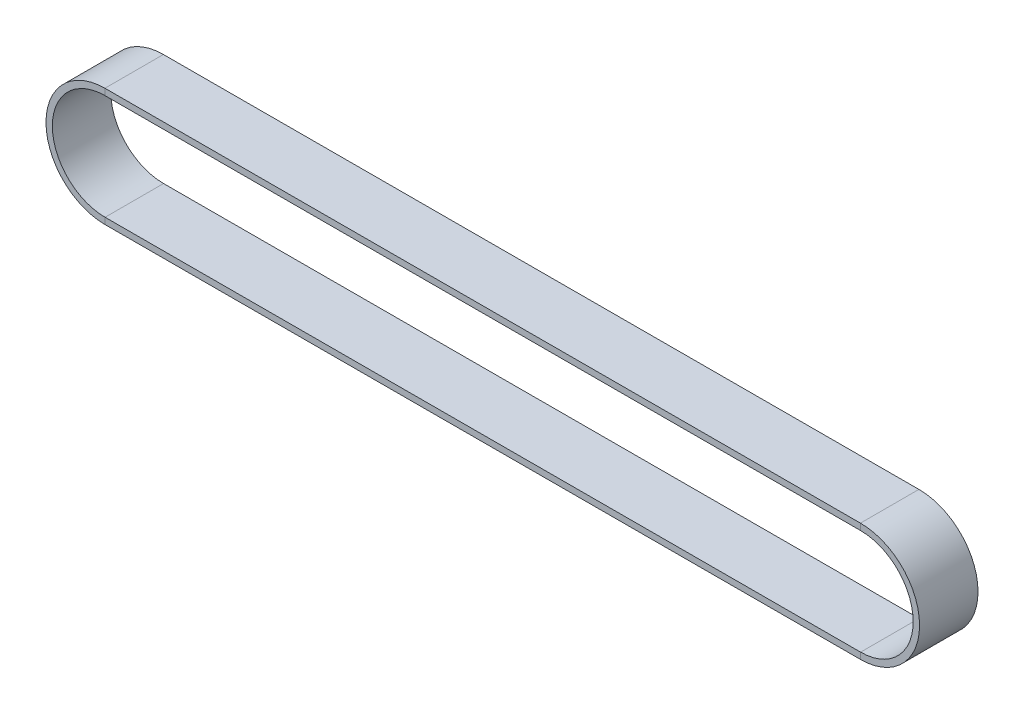
SolidWorks part; units mm, degrees
ref_plane "Front Plane" through (0, 0, 0) normal (0, 0, 1) x (1, 0, 0)
ref_plane "Top Plane" through (0, 0, 0) normal (0, 1, 0) x (1, 0, 0)
ref_plane "Right Plane" through (0, 0, 0) normal (1, 0, 0) x (0, 0, -1)
sketch "Sketch1" plane through (0, 0, 0) normal (0, 0, 1) x (1, 0, 0)
  line L0 (0, 9.2611) -> (132.9035, 9.4611)
  line L1 (132.9314, -9.0611) -> (0.0279, -9.2611)
  circle A0 centre (0, 0) radius 9.2611 construction
  circle A1 centre (132.9174, 0.2) radius 9.2611 construction
  arc A2 (0, 9.2611) -> (0.0279, -9.2611) centre (0.0139, 0) ccw
  arc A3 (132.9035, 9.4611) -> (132.9314, -9.0611) centre (132.9175, 0.2) cw
ref_plane "Plane2" through (0, 9.0985, 0) normal (0, 1, 0) x (1, 0, 0)
ref_plane "Plane3" through (0, 0, 0) normal (-1, 0, 0) x (0, 0, 1)
sketch "Sketch4" plane through (0, 0, 0) normal (-1, 0, 0) x (0, 0, 1)
  line L0 (10.2819, 9.2611) -> (10.2819, -9.2611) construction
  line L1 (0, 9.2611) -> (10.2819, 9.2611)
  line L2 (0, 9.2611) -> (0, 10.3811)
  line L3 (0, 10.3811) -> (10.2819, 10.3811)
  line L4 (10.2819, 9.2611) -> (10.2819, 10.3811)
  dimension "D1" = 1.12
sweep "Sweep1" add profiles "Sketch4" path "Sketch1"
